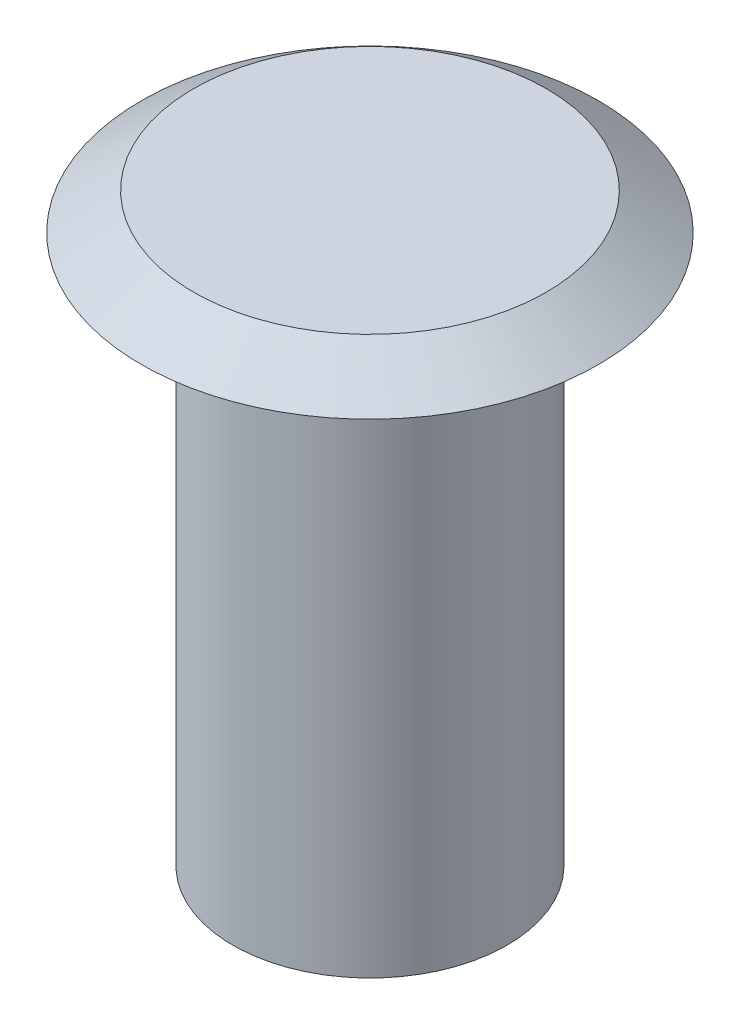
SolidWorks part; units mm, degrees
ref_plane "前视基准面" through (0, 0, 0) normal (0, 0, 1) x (1, 0, 0)
ref_plane "上视基准面" through (0, 0, 0) normal (0, 1, 0) x (1, 0, 0)
ref_plane "右视基准面" through (0, 0, 0) normal (1, 0, 0) x (0, 0, -1)
other "Configuration Table"
sketch "草图1" plane through (0, 0, 0) normal (0, 0, 1) x (1, 0, 0)
  line L0 (0, 0) -> (0, 6.4) construction
  line L1 (0, 6.4) -> (-1.9287, 6.4)
  line L2 (-1.9287, 6.4) -> (-2.5, 6)
  line L3 (-2.5, 6) -> (-1.5, 6)
  line L4 (-1.5, 6) -> (-1.5, 0)
  line L5 (-1.5, 0) -> (-0.6, 0)
  line L6 (-0.6, 0) -> (-0.6, 4)
  line L7 (-0.6, 4) -> (0, 4)
  line L8 (0, 4) -> (0, 6.4)
  dimension "D1" = 1.2
  dimension "D2" = 3
  dimension "D3" = 6
  dimension "D4" = 4
  dimension "D5" = 0.4
  dimension "D6" = 145
  dimension "D7" = 5
revolve "旋转1" add sketch "草图1" angle 360 about L0
